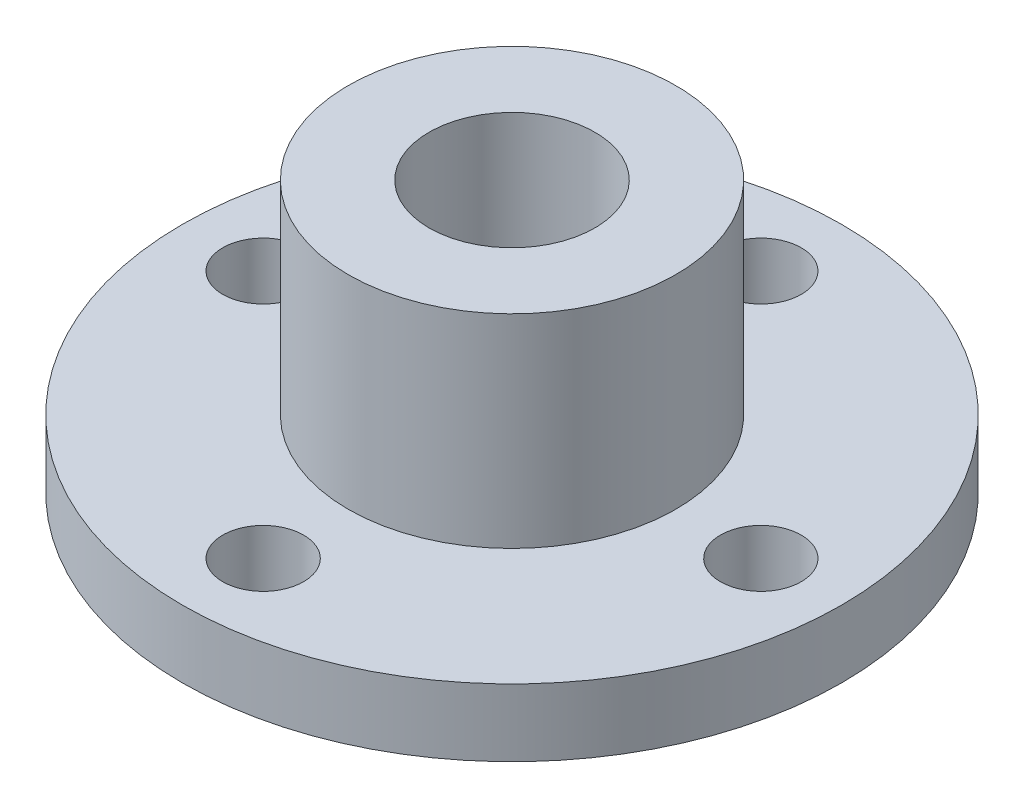
SolidWorks part; units mm, degrees
ref_plane "Front Plane" through (0, 0, 0) normal (0, 0, 1) x (1, 0, 0)
ref_plane "Top Plane" through (0, 0, 0) normal (0, 1, 0) x (1, 0, 0)
ref_plane "Right Plane" through (0, 0, 0) normal (1, 0, 0) x (0, 0, -1)
sketch "Sketch1" plane through (0, 0, 0) normal (0, 1, 0) x (1, 0, 0)
  circle A0 centre (0, 0) radius 4
  circle A1 centre (0, 0) radius 15.9
  dimension "D1" = 8
  dimension "D2" = 31.8
extrude "Boss-Extrude1" add sketch "Sketch1" along normal blind 13.05
sketch "Sketch2" plane through (0, 13.05, 0) normal (0, 1, 0) x (1, 0, 0)
  circle A0 centre (0, 0) radius 7.9
  circle A1 centre (0, 0) radius 15.9
  dimension "D1" = 15.8
extrude "Cut-Extrude1" cut sketch "Sketch2" against normal blind 9.8
sketch "Sketch3" plane through (0, 3.25, 0) normal (0, 1, 0) x (1, 0, 0)
  circle A0 centre (0, 12) radius 1.95
  circle A1 centre (12, 0) radius 1.95
  circle A2 centre (0, -12) radius 1.95
  circle A3 centre (-12, 0) radius 1.95
  dimension "D1" = 3.9
  dimension "D2" = 12
  dimension "D3" = 4
extrude "Cut-Extrude2" cut sketch "Sketch3" against normal blind 9.8
